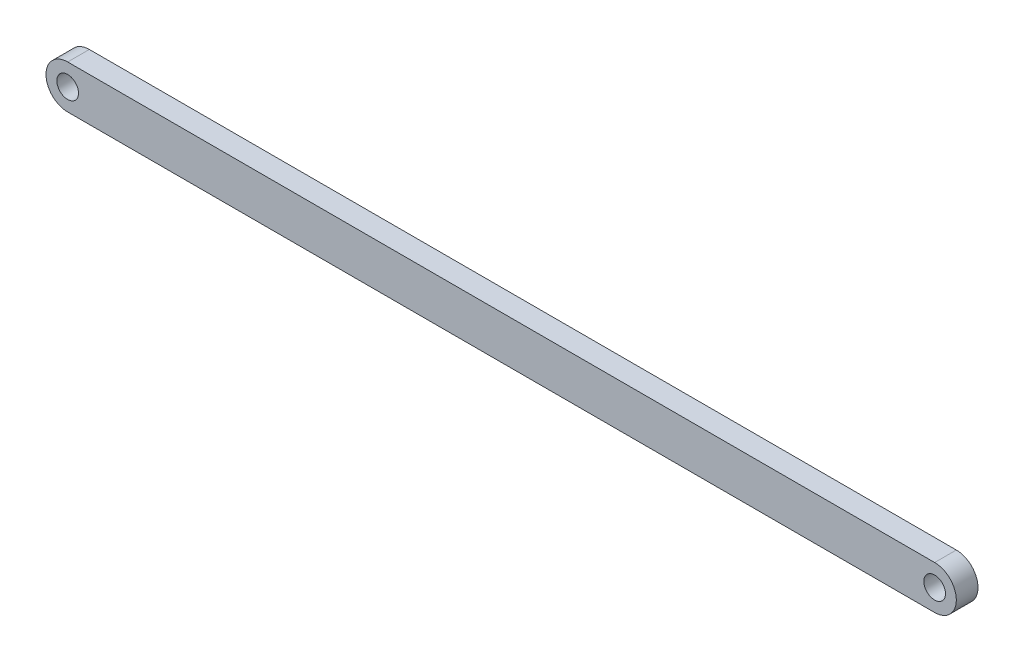
SolidWorks part; units mm, degrees
ref_plane "前视基准面" through (0, 0, 0) normal (0, 0, 1) x (1, 0, 0)
ref_plane "上视基准面" through (0, 0, 0) normal (0, 1, 0) x (1, 0, 0)
ref_plane "右视基准面" through (0, 0, 0) normal (1, 0, 0) x (0, 0, -1)
other "Configuration Table"
sketch "草图1" plane through (0, 0, 0) normal (0, 0, 1) x (1, 0, 0)
  line L0 (0, 5) -> (200, 5)
  line L1 (0, -5) -> (200, -5)
  circle A0 centre (0, 0) radius 2.5
  arc A1 (0, 5) -> (0, -5) centre (0, 0) ccw
  arc A4 (200, -5) -> (200, 5) centre (200, 0) ccw
  circle A5 centre (200, 0) radius 2.5
  dimension "D2" = 5
  dimension "D3" = 5
  dimension "D4" = 5
  dimension "D1" = 200
extrude "凸台-拉伸2" add sketch "草图1" along normal blind 5
